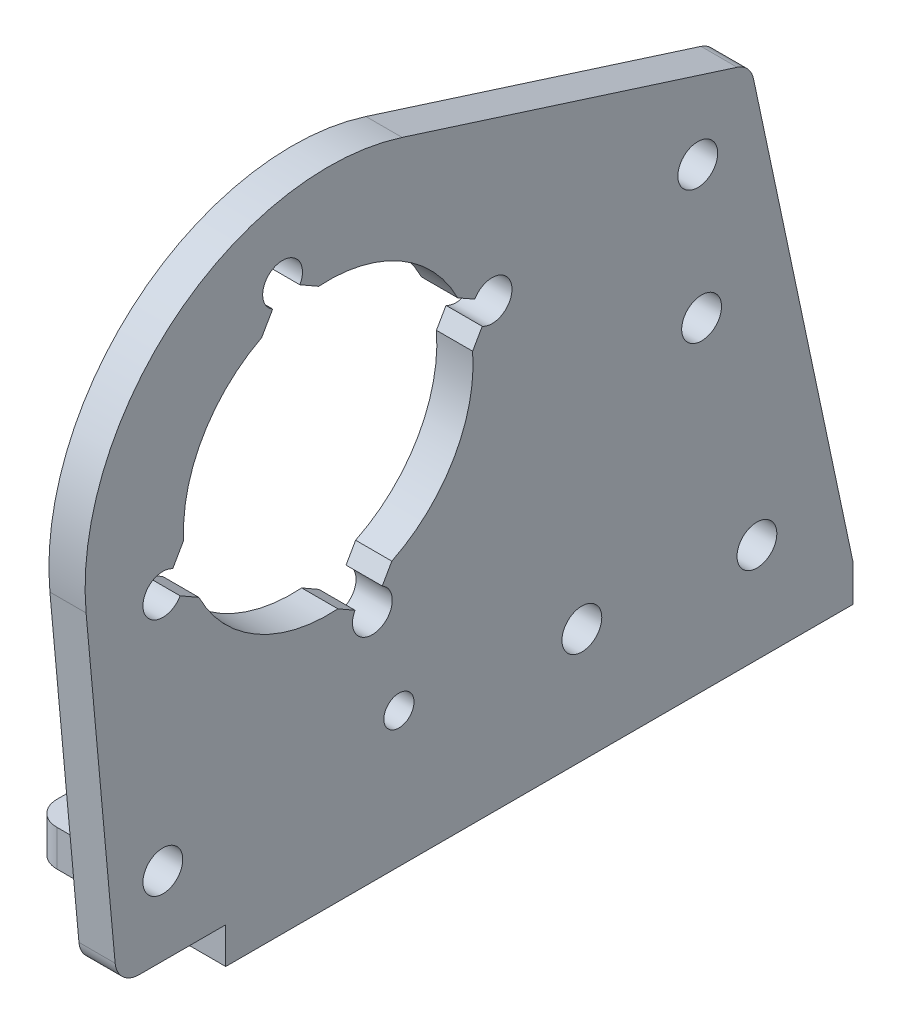
SolidWorks part; units mm, degrees
ref_plane "前视基准面" through (0, 0, 0) normal (0, 0, 1) x (1, 0, 0)
ref_plane "上视基准面" through (0, 0, 0) normal (0, 1, 0) x (1, 0, 0)
ref_plane "右视基准面" through (0, 0, 0) normal (1, 0, 0) x (0, 0, -1)
sketch "草图1" plane through (0, 0, 0) normal (1, 0, 0) x (0, 0, -1)
  line L0 (0, 53) -> (70, 53)
  line L2 (35, 53) -> (35, 13)
  line L3 (0, 0) -> (0, 53)
  line L4 (35, 53) -> (70, 53)
  line L5 (8.75, 48) -> (13.7114, 56.6824)
  line L7 (13.7114, 56.6824) -> (48.4411, 36.8369)
  line L8 (43.4797, 28.1544) -> (48.4411, 36.8369)
  line L9 (52.5, 53) -> (16.7923, 64.3795)
  line L10 (0, 13) -> (61, 13)
  line L11 (8.75, 48) -> (3.7886, 39.3176)
  line L12 (43.4797, 28.1544) -> (38.5183, 19.472)
  line L14 (3.7886, 39.3176) -> (38.5183, 19.472)
  line L15 (0, 13) -> (-3.3134, 49.2816)
  line L16 (31.0763, 46.7597) -> (21.1535, 29.3948)
  line L17 (70, 13) -> (61, 13)
  line L18 (52.5, 53) -> (61, 13)
  circle A0 centre (13.7114, 56.6824) radius 1.65
  circle A1 centre (31.0763, 46.7597) radius 1.65
  circle A2 centre (48.4411, 36.8369) radius 1.65
  circle A3 centre (21.1535, 29.3948) radius 1.65
  circle A4 centre (3.7886, 39.3176) radius 1.65
  circle A5 centre (38.5183, 19.472) radius 1.65
  circle A6 centre (17.4998, 42.9997) radius 12
  circle A7 centre (17.4998, 42.9997) radius 20.1556
  circle A8 centre (48.125, 48) radius 1.65
  circle A9 centre (23.3549, 21.1974) radius 1.25
  circle A10 centre (53.0261, 18.2423) radius 1.65
  circle A11 centre (3.7886, 19.472) radius 1.65
  dimension "D1" = 13
other "对齐组1"
extrude "凸台-拉伸4" add sketch "草图1" along normal blind 3
sketch "草图4" plane through (3, 0, 0) normal (1, 0, 0) x (0, 0, -1)
  line L0 (0, 13) -> (9, 13)
  line L1 (0, 13) -> (61, 13) construction
  line L2 (9, 13) -> (61, 13)
  line L3 (9, 13) -> (9, 10)
  line L4 (61, 13) -> (61, 10)
  line L5 (9, 10) -> (61, 10)
  line M2 (0, 13) -> (61, 13)
extrude "凸台-拉伸6" add sketch "草图4" against normal blind 16 contours L3 L5 L4 M2
sketch "草图3" plane through (0, 13, 0) normal (0, 1, 0) x (1, 0, 0)
  circle A9 centre (-8.6, 56.35) radius 1.65
  circle A11 centre (-8.6, 47.65) radius 1.65
  circle A14 centre (-8.6, 22.3) radius 1.65
  circle A15 centre (-8.6, 13.6) radius 1.65
extrude "切除-拉伸1" cut sketch "草图3" against normal blind 22 and the other way through all
fillet "圆角1" radius 2 4 edges at (1.5, 13, 0) (-13, 11.5, -9) (-13, 11.5, -61)
